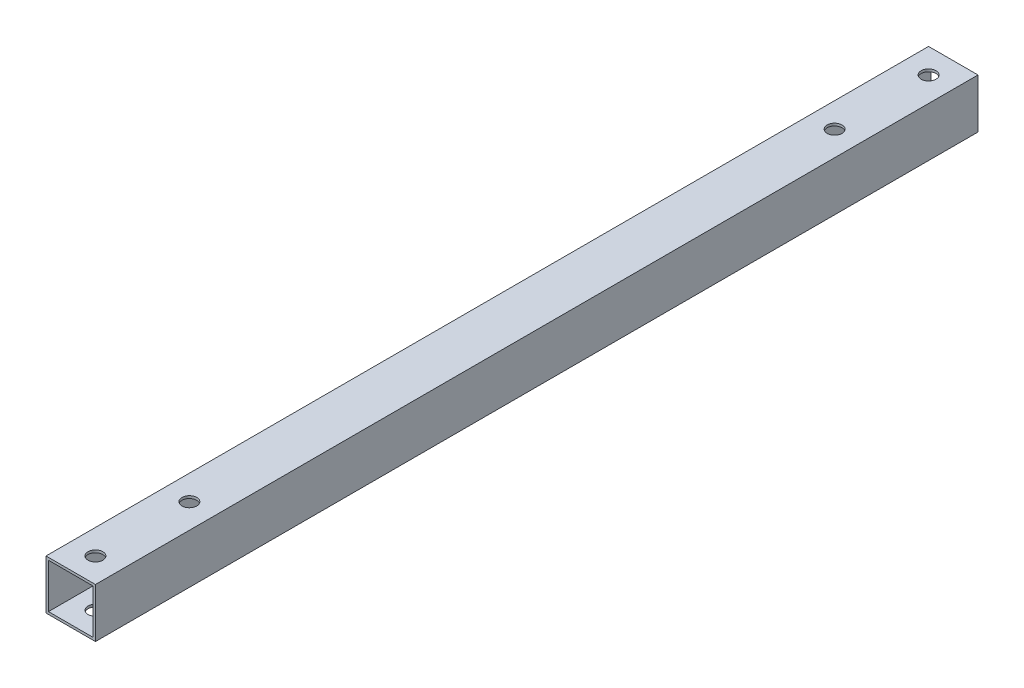
SolidWorks part; units mm, degrees
ref_plane "前基準面" through (0, 0, 0) normal (0, 0, 1) x (1, 0, 0)
ref_plane "上基準面" through (0, 0, 0) normal (0, 1, 0) x (1, 0, 0)
ref_plane "右基準面" through (0, 0, 0) normal (1, 0, 0) x (0, 0, -1)
sketch "草圖1" plane through (0, 0, 0) normal (0, 0, 1) x (1, 0, 0)
  line L1 (-5, 5) -> (5, 5)
  line L2 (-5, 5) -> (-5, -5)
  line L3 (-5, -5) -> (5, -5)
  line L4 (5, 5) -> (5, -5)
  line L5 (-5, 5) -> (5, -5) construction
  line L6 (-5, -5) -> (5, 5) construction
  line L7 (-4.5, 4.5) -> (4.5, 4.5)
  line L8 (-4.5, 4.5) -> (-4.5, -4.5)
  line L9 (-4.5, -4.5) -> (4.5, -4.5)
  line L10 (4.5, 4.5) -> (4.5, -4.5)
  line L11 (-4.5, 4.5) -> (4.5, -4.5) construction
  line L12 (-4.5, -4.5) -> (4.5, 4.5) construction
  point P0 (0, 0)
  point P6 (0, 0)
  dimension "D1" = 10
  dimension "D2" = 0.5
extrude "填料-伸長1" add sketch "草圖1" along normal blind 178.5
sketch "草圖2" plane through (0, 5, 0) normal (0, 1, 0) x (1, 0, 0)
  line L0 (0, 0) -> (0, -150) construction
  line L3 (5, -178.5) -> (-5, -178.5) construction
  circle A0 centre (0, -5) radius 1.5
  circle A1 centre (0, -24) radius 1.5
  circle A2 centre (0, -154.5) radius 1.5
  circle A3 centre (0, -173.5) radius 1.5
  dimension "D1" = 3
  dimension "D2" = 3
  dimension "D6" = 3
  dimension "D7" = 3
  dimension "D3" = 19
  dimension "D4" = 5
  dimension "D5" = 5
  dimension "D8" = 19
extrude "除料-伸長1" cut sketch "草圖2" against normal through all
